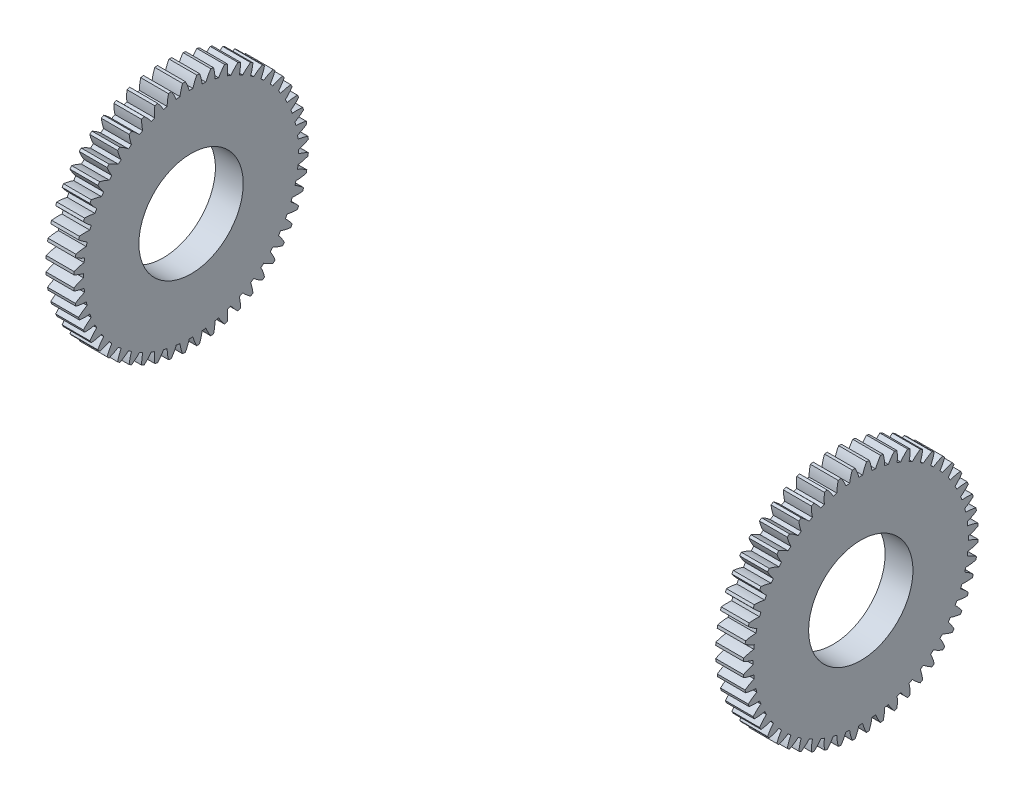
SolidWorks part; units mm, degrees
material "CF Nylon"
ref_plane "Plane1" through (0, 0, 0) normal (0, 0, 1) x (1, 0, 0)
ref_plane "Plane2" through (0, 0, 0) normal (0, 1, 0) x (1, 0, 0)
ref_plane "Plane3" through (0, 0, 0) normal (1, 0, 0) x (0, 0, -1)
other "Configuration Table"
ref_plane "Plane5" through (58.6, 0, 0) normal (1, 0, 0) x (0, 0, -1)
sketch "HoldingSke" plane through (0, 0, 0) normal (0, 1, 0) x (1, 0, 0)
  line L0 (0, 0) -> (500.4096, -640.4951)
  line L1 (-15, 0) -> (100, 0) construction
  line L2 (0, 0) -> (-2.1039, 2.3779)
  line L3 (0, 0) -> (-11.863, 4.5341)
  line L4 (0, 0) -> (5.3169, 6.8053)
  line L5 (0, 0) -> (-47.5972, -17.7524)
  line L6 (0, 0) -> (-4.2111, -2.8413)
  line L7 (-2.1039, 2.3779) -> (8.8308, 51.9871)
  line L8 (-76.2, 54.61) -> (-75.184, 54.61)
  line L9 (-71.009, 38.7566) -> (-53.1078, 45.2721)
  line L10 (-76.2, 71.12) -> (104.1128, 71.12)
  line L11 (0, 0) -> (-5.08, 0)
  line L12 (-76.2, 101.6) -> (-76.1716, 101.6)
  line L13 (24.9733, 27.94) -> (52.9518, 28.4284)
  line L14 (24.9733, 27.94) -> (25.0241, 27.9398)
  line L15 (24.9733, 27.94) -> (100.4021, 29.52)
  circle A0 centre (0, 0) radius 0.3969
  circle A1 centre (0, 0) radius 19.6342
  circle A2 centre (0, 0) radius 38.1
  circle A3 centre (0, 0) radius 0.3969
  dimension "MHD" = 39.2684
  dimension "Hub_dia" = 76.2
  dimension "Bore" = 0.7937
  dimension "MBD" = 0.7937
  dimension "Num_teeth" = 52
  dimension "Pitch" = 812.8
  dimension "Overall_len" = 50.8
  dimension "Show_teeth" = 52
  dimension "Thickness" = 5.08
  dimension "OAL" = 50.8001
  dimension "T_dim" = 1.016
  dimension "Ap" = 20
  dimension "H" = 19.05
  dimension "Pitch_radius" = 180.3128
  dimension "Width" = 5.08
  dimension "Backlash" = 0.0284
  dimension "Addendum_fac" = 1
  dimension "Dedendum_fac" = 1.2
  dimension "Clearance_fac" = 0.2
  dimension "Dedendum_add" = 0.0508
sketch "BasProSke" plane through (0, 0, 0) normal (0, 1, 0) x (1, 0, 0)
  line L0 (-10, 0) -> (73.8635, 0) construction
  line L1 (58.6, 0) -> (58.6, 21.4312)
  line L2 (58.6, 0) -> (63.68, 0)
  line L3 (63.68, 0) -> (63.68, 21.4312)
  line L4 (63.68, 21.4312) -> (58.6, 21.4312)
  line L6 (58.6, -16.025) -> (58.6, 16.025) construction
  point P3 (57.33, 21.4312)
  point P5 (58.6, 0)
  point P10 (73.8635, 0)
  dimension "Thickness" = 5.08
  dimension "Diameter" = 42.8625
revolve "Base-Revolve" add sketch "BasProSke" angle 360 about L0
sketch "TooCutSke" plane through (0, 0, 0) normal (1, 0, 0) x (0, 0, -1)
  line L1 (0, 0) -> (0, 107) construction
  line L2 (0, 0) -> (-0.6731, 20.6265) construction
  line L3 (0, 0) -> (-2.4912, 41.1838) construction
  line L4 (-0.6731, 20.6265) -> (-1.2456, 20.5919) construction
  arc A0 (0.3404, 19.6312) -> (-0.3404, 19.6312) centre (0, 0) ccw
  arc A1 (1.0518, 21.4309) -> (-1.0518, 21.4309) centre (0, 0) ccw
  circle A2 centre (0, 0) radius 20.6375 construction
  circle A3 centre (0, 0) radius 19.3929 construction
  arc A4 (-0.3404, 19.6312) -> (-1.0518, 21.4309) centre (-8.3202, 17.5174) ccw
  arc A5 (1.0518, 21.4309) -> (0.3404, 19.6312) centre (8.3202, 17.5174) ccw
  dimension "Root_dia" = 39.2684
  dimension "Overcut_dia" = 42.9133
  dimension "Pitch_dia" = 41.275
  dimension "Base_dia" = 38.7858
  dimension "Flank_rad" = 8.255
  dimension "Half_ang" = 3.462
  dimension "Half_CT" = 0.5735
extrude "ToothCut" cut sketch "TooCutSke" along normal through all
fillet "Breaks" [suppressed] radius 0.0159
fillet "RootFillets" [suppressed] radius 0.2095
pattern_circular "TeethCuts" count 52 every 6.923 about axis through (-10, 0, 0) along (1, 0, 0) of "ToothCut", "RootFillets", "Breaks"
sketch "HubNeaOneSke" plane through (58.6, 0, 0) normal (-1, 0, 0) x (0, 0, 1)
  circle A0 centre (0, 0) radius 19.6342
  dimension "Diameter" = 39.2684
extrude "HubNearOne" [suppressed] add sketch "HubNeaOneSke" along normal blind 45.7201
sketch "HubNeaBotSke" plane through (58.6, 0, 0) normal (-1, 0, 0) x (0, 0, 1)
  circle A0 centre (0, 0) radius 19.6342
  dimension "Diameter" = 39.2684
extrude "HubNearBoth" [suppressed] add sketch "HubNeaBotSke" along normal blind 22.86
ref_plane "FarPln" through (5.08, 0, 0) normal (1, 0, 0) x (0, 0, -1)
sketch "HubFarSke" plane through (5.08, 0, 0) normal (1, 0, 0) x (0, 0, -1)
  circle A0 centre (0, 0) radius 19.6342
  dimension "Diameter" = 39.2684
extrude "HubFar" [suppressed] add sketch "HubFarSke" along normal blind 22.86
sketch "BorSke" plane through (58.6, 0, 0) normal (1, 0, 0) x (0, 0, -1)
  circle A0 centre (0, 0) radius 9.525 construction
  circle A2 centre (0, 0) radius 9.525
extrude "Bore" cut sketch "BorSke" along normal mid plane 101.6001
sketch "KeySke" plane through (0, 0, 0) normal (1, 0, 0) x (0, 0, -1)
  line L0 (-0.127, 0) -> (-0.127, 0.6191)
  line L1 (-0.127, 0.6191) -> (0.127, 0.6191)
  line L2 (0.127, 0.6191) -> (0.127, 0)
  line L3 (0, 0) -> (0, 34) construction
  line L4 (-0.127, 0) -> (0.127, 0)
  dimension "Offset" = 0.6191
  dimension "Width" = 0.254
extrude "Keyway" [suppressed] cut sketch "KeySke" along normal mid plane 101.6001
pattern_circular "Keyway2" [suppressed] count 2 every 90 about axis through (-10, 0, 0) along (1, 0, 0)
ref_plane "Plane4" through (-52.25, 0, 0) normal (1, 0, 0) x (0, 0, -1)
mirror "Mirror1" about plane through (0, 0, 0) normal (1, 0, 0) of bodies 103 104
equation "' \"Pitch@HoldingSke\" = 4"
equation "' \"Num_teeth@HoldingSke\" = 12"
equation "' \"Ap@HoldingSke\" =  20"
equation "' \"Ap@HoldingSke\" = 20"
equation "' \"Width@HoldingSke\" = 0.5"
equation "' \"Hub_dia@HoldingSke\"= 1"
equation "' \"Hub_dia@HoldingSke\" = 1"
equation "' \"Overall_len@HoldingSke\" = 1.0"
equation "' \"Bore@HoldingSke\" = 0.75"
equation "' \"T_dim@HoldingSke\" = 0.85"
equation "' \"Width@KeySke\" = 0.25"
equation "' \"Show_teeth@HoldingSke\" = 13"
equation "' \"Backlash@HoldingSke\" = 0.009"
equation "' \"Addendum_fac@HoldingSke\" = 1.0"
equation "' \"Dedendum_fac@HoldingSke\" = 1.25"
equation "' \"Dedendum_add@HoldingSke\" = 0.00005"
equation "' \"Clearance_fac@HoldingSke\" = 0.25"
equation "' \"Pitch@HoldingSke\" = 0.5"
equation "' \"Num_teeth@HoldingSke\" = 23"
equation "' \"Show_teeth@HoldingSke\" = 23"
equation "' \"Backlash@HoldingSke\" = 0.0375"
equation "\"Overcut_dia@TooCutSke\" = (\"Num_teeth@HoldingSke\" + 2 * \"Addendum_fac@HoldingSke\") / \"Pitch@HoldingSke\" + 0.002"
equation "\"Pitch_dia@TooCutSke\" = \"Num_teeth@HoldingSke\" / \"Pitch@HoldingSke\""
equation "\"Base_dia@TooCutSke\" = \"Num_teeth@HoldingSke\" / \"Pitch@HoldingSke\" * cos((\"Ap@HoldingSke\"  * 3.14159265 / 180))"
equation "\"Root_dia@TooCutSke\" = (\"Num_teeth@HoldingSke\" + 2) / \"Pitch@HoldingSke\" - 2 * (\"Addendum_fac@HoldingSke\" + \"Dedendum_fac@HoldingSke\") / \"Pitch@HoldingSke\" - \"Dedendum_add@HoldingSke\" * 2"
equation "\"Half_ang@TooCutSke\" = 180 / \"Num_teeth@HoldingSke\""
equation "\"Half_CT@TooCutSke\" = \"Num_teeth@HoldingSke\" / \"Pitch@HoldingSke\" * sin((3.14159265 / 2 / \"Num_teeth@HoldingSke\")) / 2 - 7 * \"Backlash@HoldingSke\" / 4"
equation "\"Flank_rad@TooCutSke\" = \"Num_teeth@HoldingSke\" / \"Pitch@HoldingSke\" / 5"
equation "\"Radius@RootFillets\" = \"Clearance_fac@HoldingSke\" / \"Pitch@HoldingSke\" + \"Dedendum_add@HoldingSke\""
equation "\"Break_rad@Breaks\" = 0.02 / \"Pitch@HoldingSke\""
equation "\"Thickness@HoldingSke\" = \"Width@HoldingSke\""
equation "\"OAL@HoldingSke\" = \"Thickness@HoldingSke\""
equation "\"MHD@HoldingSke\" = (\"Num_teeth@HoldingSke\" + 2) / \"Pitch@HoldingSke\" - 2 * (\"Addendum_fac@HoldingSke\" + \"Dedendum_fac@HoldingSke\")  / \"Pitch@HoldingSke\" - \"Dedendum_add@HoldingSke\" * 2"
equation "\"MBD@HoldingSke\" = (\"Num_teeth@HoldingSke\" + 2) / \"Pitch@HoldingSke\" - 2 * (\"Addendum_fac@HoldingSke\" + \"Dedendum_fac@HoldingSke\")  / \"Pitch@HoldingSke\" - \"Dedendum_add@HoldingSke\" * 2 - 0.002"
equation "\"MHD@HoldingSke\" = ((sgn( \"MHD@HoldingSke\" - \"Hub_dia@HoldingSke\" )-1)*( \"MHD@HoldingSke\" - \"Hub_dia@HoldingSke\" ))/-2+ \"Hub_dia@HoldingSke\""
equation "\"MBD@HoldingSke\" = ((sgn( \"MBD@HoldingSke\" - \"Bore@HoldingSke\" )-1)*( \"MBD@HoldingSke\" - \"Bore@HoldingSke\" ))/-2+ \"Bore@HoldingSke\""
equation "\"OAL@HoldingSke\" = ((sgn( \"OAL@HoldingSke\" - \"Overall_len@HoldingSke\" )+1)*( \"OAL@HoldingSke\" - \"Overall_len@HoldingSke\" ))/2 + \"Overall_len@HoldingSke\" + 0.000002"
equation "\"Num_teeth@TeethCuts\" = int( \"Show_teeth@HoldingSke\" ) + 1"
equation "\"Num_teeth@TeethCuts\" = ((sgn( \"Num_teeth@TeethCuts\" - \"Num_teeth@HoldingSke\" )-1)*( \"Num_teeth@TeethCuts\" - \"Num_teeth@HoldingSke\" ))/-2+ \"Num_teeth@HoldingSke\""
equation "\"Num_teeth@TeethCuts\" = ((sgn( \"Num_teeth@TeethCuts\" - 2.0)+1)*( \"Num_teeth@TeethCuts\" - 2.0))/2 +2.0"
equation "\"Angle@TeethCuts\" = 360.0 / \"Num_teeth@HoldingSke\""
equation "\"Diameter@BasProSke\" = (\"Num_teeth@HoldingSke\" + 2 * \"Addendum_fac@HoldingSke\") / \"Pitch@HoldingSke\""
equation "\"Thickness@BasProSke\"  = \"Thickness@HoldingSke\""
equation "' \"Fillet_rad@BasProSke\" =  \"Thickness@HoldingSke\" * 0.05"
equation "' \"Fillet_rad@BasProSke\" = \"Thickness@HoldingSke\" * 0.05"
equation "\"MHD@HoldingSke\" = ((sgn( \"MHD@HoldingSke\" - \"Root_dia@TooCutSke\" )-1)*( \"MHD@HoldingSke\" - \"Root_dia@TooCutSke\" ))/-2+ \"Root_dia@TooCutSke\""
equation "\"Diameter@HubNeaOneSke\" = \"MHD@HoldingSke\""
equation "\"Length@HubNearOne\" = \"OAL@HoldingSke\" - \"Thickness@BasProSke\""
equation "\"Diameter@HubNeaBotSke\" = \"MHD@HoldingSke\""
equation "\"Length@HubNearBoth\" = ( \"OAL@HoldingSke\" - \"Thickness@BasProSke\" ) / 2.0"
equation "\"Thickness@FarPln\" = \"Thickness@BasProSke\""
equation "\"Diameter@HubFarSke\" = \"MHD@HoldingSke\""
equation "\"Length@HubFar\" = ( \"OAL@HoldingSke\" - \"Thickness@BasProSke\" ) / 2.0"
equation "\"D1@Bore\" = \"OAL@HoldingSke\" * 2.0"
equation "\"D1@Keyway\" = \"OAL@HoldingSke\" * 2.0"
equation "\"Offset@KeySke\" = \"T_dim@HoldingSke\" - \"MBD@HoldingSke\" / 2.0"
